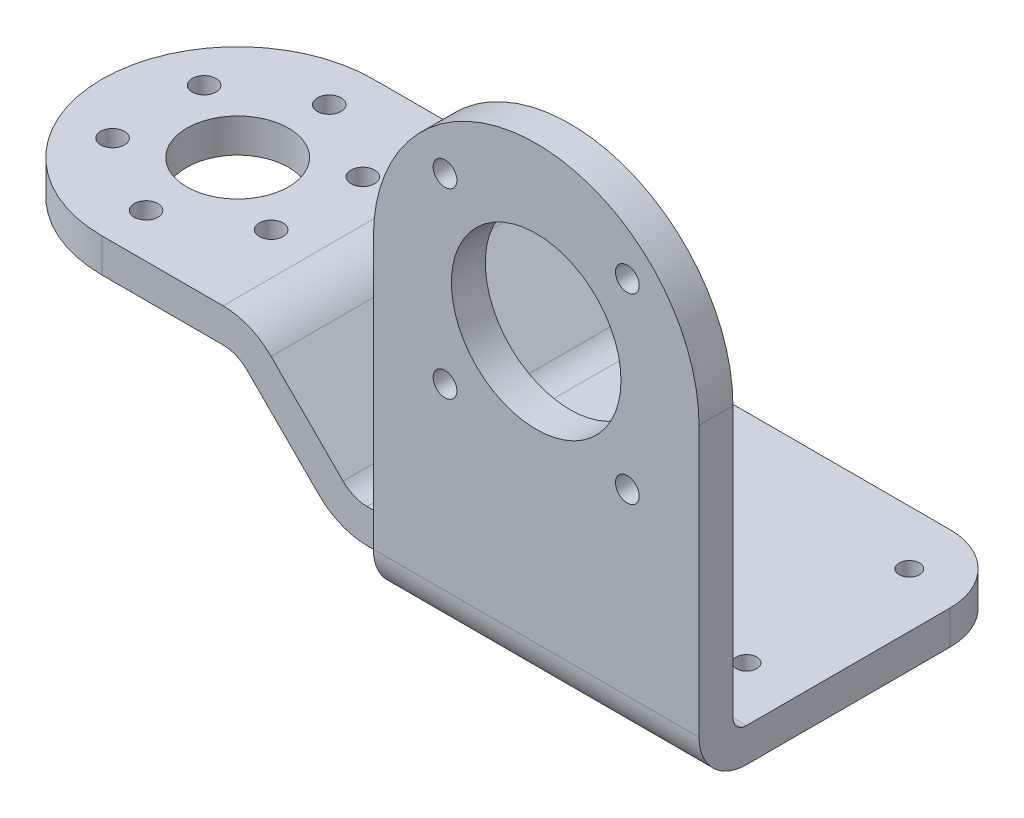
SolidWorks part; units mm, degrees
material "AISI 304"
ref_plane "前视基准面" through (0, 0, 0) normal (0, 0, 1) x (1, 0, 0)
ref_plane "上视基准面" through (0, 0, 0) normal (0, 1, 0) x (1, 0, 0)
ref_plane "右视基准面" through (0, 0, 0) normal (1, 0, 0) x (0, 0, -1)
sketch "草图1" plane through (0, 0, 0) normal (0, 1, 0) x (1, 0, 0)
  line L0 (0, 20) -> (95, 20)
  line L1 (95, 20) -> (95, -20)
  line L2 (95, -20) -> (0, -20)
  line L3 (95, -20) -> (47, -20)
  line L4 (47, -20) -> (47, -27)
  line L5 (47, -27) -> (95, -27)
  line L6 (95, -27) -> (95, -20)
  circle A0 centre (0, 0) radius 20
  dimension "D1" = 40
  dimension "D2" = 95
  dimension "D3" = 48
  dimension "D4" = 7
extrude "凸台-拉伸1" add sketch "草图1" along normal blind 5
sketch "草图3" plane through (0, 5, 0) normal (0, 1, 0) x (1, 0, 0)
  circle A0 centre (0, 0) radius 13.5 construction
  circle A1 centre (0, 13.5) radius 1.75
  circle A2 centre (11.6913, 6.75) radius 1.75
  circle A3 centre (11.6913, -6.75) radius 1.75
  circle A4 centre (0, -13.5) radius 1.75
  circle A5 centre (-11.6913, -6.75) radius 1.75
  circle A6 centre (-11.6913, 6.75) radius 1.75
  point P18 (0, 0)
  dimension "D1" = 27
  dimension "D2" = 3.5
  dimension "D3" = 6
extrude "切除-拉伸1" cut sketch "草图3" against normal blind 11
sketch "草图8" plane through (0, 0, 27) normal (0, 0, 1) x (1, 0, 0)
  line L0 (71, 0) -> (71, 46.8) construction
  line L1 (47, 0) -> (95, 0) construction
  line L2 (95, 46.8) -> (95, 0)
  line L3 (95, 0) -> (47, 0)
  line L4 (47, 5) -> (47, 0) construction
  line L5 (47, 0) -> (47, 46.8)
  line L6 (47, 5) -> (95, 5) construction
  arc A0 (95, 46.8) -> (47, 46.8) centre (71, 46.8) ccw
  dimension "D1" = 48
  dimension "D2" = 41.8
extrude "凸台-拉伸3" add sketch "草图8" against normal blind 5
fillet "圆角8" radius 2 1 edges at (71, 5, 22)
fillet "圆角9" radius 7 1 edges at (71, 0, 27)
fillet "圆角10" radius 10 1 edges at (95, 2.5, -20)
sketch "草图9" plane through (0, 0, 27) normal (0, 0, 1) x (1, 0, 0)
  line L0 (71, 65.8) -> (71, 46.8) construction
  line L1 (71, 46.8) -> (57.565, 60.235) construction
  circle A0 centre (71, 46.8) radius 19 construction
  circle A1 centre (57.565, 60.235) radius 1.75
  circle A2 centre (84.435, 60.235) radius 1.75
  circle A3 centre (84.435, 33.365) radius 1.75
  circle A4 centre (57.565, 33.365) radius 1.75
  point P16 (71, 46.8)
  dimension "D1" = 38
  dimension "D3" = 3.5
  dimension "D2" = 45
  dimension "D4" = 4
extrude "切除-拉伸2" cut sketch "草图9" against normal blind 5
sketch "草图10" plane through (0, 5, 0) normal (0, 1, 0) x (1, 0, 0)
  line L0 (0, 20) -> (50, 20)
  line L1 (0, 20) -> (85, 20) construction
  line L2 (50, 20) -> (50, -20)
  line L3 (47, -20) -> (0, -20) construction
  line L4 (50, -20) -> (-0.5467, -20)
  circle A0 centre (0, 0) radius 20
  circle A1 centre (0, 0) radius 13.5 construction
  circle A2 centre (0, 13.5) radius 1.75
  circle A3 centre (11.6913, 6.75) radius 1.75
  circle A4 centre (11.6913, -6.75) radius 1.75
  circle A5 centre (0, -13.5) radius 1.75
  circle A6 centre (-11.6913, -6.75) radius 1.75
  circle A7 centre (-11.6913, 6.75) radius 1.75
  point P20 (0, 0)
  circle M5 centre (0, 13.5) radius 1.75
  circle M6 centre (-11.6913, 6.75) radius 1.75
  circle M7 centre (-11.6913, -6.75) radius 1.75
  circle M8 centre (0, -13.5) radius 1.75
  circle M9 centre (11.6913, -6.75) radius 1.75
  circle M10 centre (11.6913, 6.75) radius 1.75
  line M13 (85, 20) -> (0, 20)
  arc M14 (0, 20) -> (0, -20) centre (0, 0) ccw
  line M15 (0, -20) -> (47, -20)
  dimension "D1" = 40
  dimension "D2" = 3.5
  dimension "D3" = 6
  dimension "D4" = 50
extrude "凸台-拉伸4" add sketch "草图10" along normal blind 15 contours A0 M14 M6 M8 M10 M9 M7 M5 | A0 L2 M15 M13
sketch "草图11" plane through (0, 0, -20) normal (0, 0, -1) x (-1, 0, 0)
  line L0 (-37, 5) -> (-22, 20)
  line L1 (-50, 20) -> (0, 20) construction
  line L2 (-34.9289, 0) -> (-19.9289, 15)
  line L3 (0, 0) -> (-85, 0) construction
  line L4 (-22, 20) -> (20, 20)
  line L5 (20, 0) -> (20, 20) construction
  line L6 (20, 20) -> (0, 20) construction
  line L7 (-19.9289, 15) -> (20, 15)
  line L8 (20, 20) -> (20, 15)
  line L9 (-50, 20) -> (-50, 5) construction
  line L10 (20, 20) -> (-50, 20)
  line L11 (20, 20) -> (20, 0)
  line L12 (20, 0) -> (-50, 0)
  line L13 (-50, 20) -> (-50, 0)
  line L14 (-47, 5) -> (-47, 7) construction
  line L15 (-50, 5) -> (-37, 5)
  line M6 (0, 0) -> (0, 20)
  line M7 (0, 20) -> (-50, 20)
  line M8 (-50, 20) -> (-50, 5)
  line M11 (-85, 0) -> (0, 0)
  dimension "D1" = 45
  dimension "D2" = 5
  dimension "D3" = 5
  dimension "D4" = 10
extrude "切除-拉伸4" cut sketch "草图11" against normal blind 40 contours L7 L2 M11 M6 | L12 L11 L7 M6 | L0 M8 M7
fillet "圆角11" radius 5 1 edges at (19.9289, 15, 0)
fillet "圆角12" radius 10 1 edges at (22, 20, 0)
fillet "圆角13" radius 10 1 edges at (34.9289, 0, 0)
fillet "圆角14" radius 5 1 edges at (37, 5, 0)
sketch "草图13" plane through (0, 0, 0) normal (0, -1, 0) x (1, 0, 0)
  line L0 (70.9645, 19.9135) -> (70.9645, -21.8266) construction
  line L2 (83.4645, 16.0355) -> (58.4645, 16.0355)
  line L3 (58.4645, 16.0355) -> (70.9645, 3.5355)
  line L6 (67.4289, 0) -> (54.9289, 12.5)
  line L10 (39.0711, 0) -> (113.5306, 0) construction
  line L11 (39.0711, 20) -> (39.0711, -20) construction
  line L12 (54.9289, 12.5) -> (54.9289, -12.5)
  line L13 (67.4289, 0) -> (54.9289, -12.5)
  line L14 (58.4645, -16.0355) -> (70.9645, -3.5355)
  line L15 (83.4645, -16.0355) -> (58.4645, -16.0355)
  line L16 (83.4645, -16.0355) -> (70.9645, -3.5355)
  line L17 (74.5, 0) -> (87, 12.5)
  line L18 (74.5, 0) -> (87, -12.5)
  line L19 (87, 12.5) -> (87, -12.5)
  line L20 (83.4645, 16.0355) -> (70.9645, 3.5355)
  line L21 (67.4289, 0) -> (70.9645, 3.5355) construction
  line L22 (67.4289, 0) -> (70.9645, -3.5355) construction
  line L24 (95, -10) -> (95, 20) construction
  line L25 (0, 0) -> (131.2782, 0) construction
  point P16 (54.9289, 0)
  point P20 (70.9645, -16.0355)
  point P24 (70.9645, 16.0355)
  dimension "D1" = 45
  dimension "D2" = 5
  dimension "D3" = 25
  dimension "D5" = 25
  dimension "D6" = 8
extrude "切除-拉伸6" [suppressed] cut sketch "草图13" against normal blind 10
fillet "圆角16" [suppressed] radius 2
sketch "草图15" [suppressed] plane through (0, 0, 0) normal (0, -1, 0) x (1, 0, 0)
  line L0 (96.8211, -17.3211) -> (48.8909, 30.6091) construction
  line L1 (66.8787, 12.6213) -> (75.9645, 3.5355) construction
  line L2 (76.1967, 0.2322) -> (93.2251, 17.2606) construction
  line L3 (47.9417, 28.0228) -> (98.8607, -22.8963) construction
  line L4 (51.1421, -20) -> (90, -20) construction
  line L5 (74.5503, -4.9497) -> (66.8787, -12.6213) construction
  line L6 (0, 0) -> (127.3157, 0) construction
  line L7 (80.9142, -1.4142) -> (88.5858, -9.0858) construction
  circle A1 centre (90.9645, -15) radius 1.5
  circle A2 centre (60.9645, -15) radius 1.5
  circle A3 centre (60.9645, 15) radius 1.5
  circle A4 centre (90.9645, 15) radius 1.5
  dimension "D1" = 3
  dimension "D2" = 5
  dimension "D3" = 2.5
  dimension "D5" = 3
  dimension "D6" = 5
  dimension "D4" = 2.5
extrude "切除-拉伸7" [suppressed] cut sketch "草图15" against normal blind 10
sketch "草图16" plane through (0, 20, 0) normal (0, 1, 0) x (1, 0, 0)
  line L0 (0, 15) -> (24.2917, 15) construction
  line L1 (17.8579, 20) -> (0, 20) construction
  line L2 (0, 0) -> (23.722, 0) construction
  circle A0 centre (19.6913, 15) radius 1.5
  circle A1 centre (11.6913, 6.75) radius 1.75 construction
  circle A2 centre (19.6913, -15) radius 1.5
  circle A3 centre (0, 0) radius 16 construction
  circle A4 centre (-16, 0) radius 1.5
  dimension "D2" = 3
  dimension "D3" = 8
  dimension "D4" = 32
  dimension "D5" = 3
  dimension "D1" = 5
extrude "切除-拉伸8" [suppressed] cut sketch "草图16" against normal blind 10
sketch "草图17" plane through (0, 20, 0) normal (0, 1, 0) x (1, 0, 0)
  circle A0 centre (0, 0) radius 7.5
  dimension "D1" = 15
extrude "切除-拉伸9" cut sketch "草图17" against normal blind 10
sketch "草图18" plane through (0, 0, 27) normal (0, 0, 1) x (1, 0, 0)
  circle A0 centre (71, 46.8) radius 12.5
  dimension "D1" = 25
extrude "切除-拉伸10" cut sketch "草图18" against normal blind 10
sketch "草图19" plane through (0, 15, 0) normal (0, -1, 0) x (1, 0, 0)
  circle A0 centre (0, 13.5) radius 3
  circle A1 centre (11.6913, 6.75) radius 3
  circle A2 centre (11.6913, -6.75) radius 3
  circle A3 centre (0, -13.5) radius 3
  circle A4 centre (-11.6913, -6.75) radius 3
  circle A5 centre (-11.6913, 6.75) radius 3
  dimension "D1" = 6
  dimension "D2" = 6
  dimension "D3" = 6
  dimension "D4" = 6
  dimension "D5" = 6
  dimension "D6" = 6
extrude "切除-拉伸11" [suppressed] cut sketch "草图19" against normal blind 3
sketch "草图20" plane through (0, 0, 27) normal (0, 0, 1) x (1, 0, 0)
  circle A0 centre (57.565, 60.235) radius 3
  circle A1 centre (84.435, 60.235) radius 3
  circle A2 centre (84.435, 33.365) radius 3
  circle A3 centre (57.565, 33.365) radius 3
  dimension "D1" = 6
  dimension "D2" = 6
  dimension "D3" = 6
  dimension "D4" = 6
extrude "切除-拉伸12" [suppressed] cut sketch "草图20" against normal blind 3
sketch "草图21" plane through (0, 0, 0) normal (0, -1, 0) x (1, 0, 0)
  line L0 (95, 20) -> (47, 20) construction
  line L1 (39.0711, 20) -> (39.0711, -20) construction
  line L2 (95, -10) -> (95, 20) construction
  line L3 (39.0711, -20) -> (85, -20) construction
  circle A0 centre (87, 12) radius 1.5
  circle A1 centre (47.0711, -12) radius 1.5
  circle A2 centre (47.0711, 12) radius 1.5
  circle A3 centre (87, -12) radius 1.5
  dimension "D7" = 3
  dimension "D8" = 3
  dimension "D9" = 3
  dimension "D11" = 8
  dimension "D12" = 3
  dimension "D1" = 8
  dimension "D2" = 8
  dimension "D3" = 8
  dimension "D4" = 8
  dimension "D5" = 8
  dimension "D6" = 8
  dimension "D10" = 8
extrude "切除-拉伸13" cut sketch "草图21" against normal blind 10
